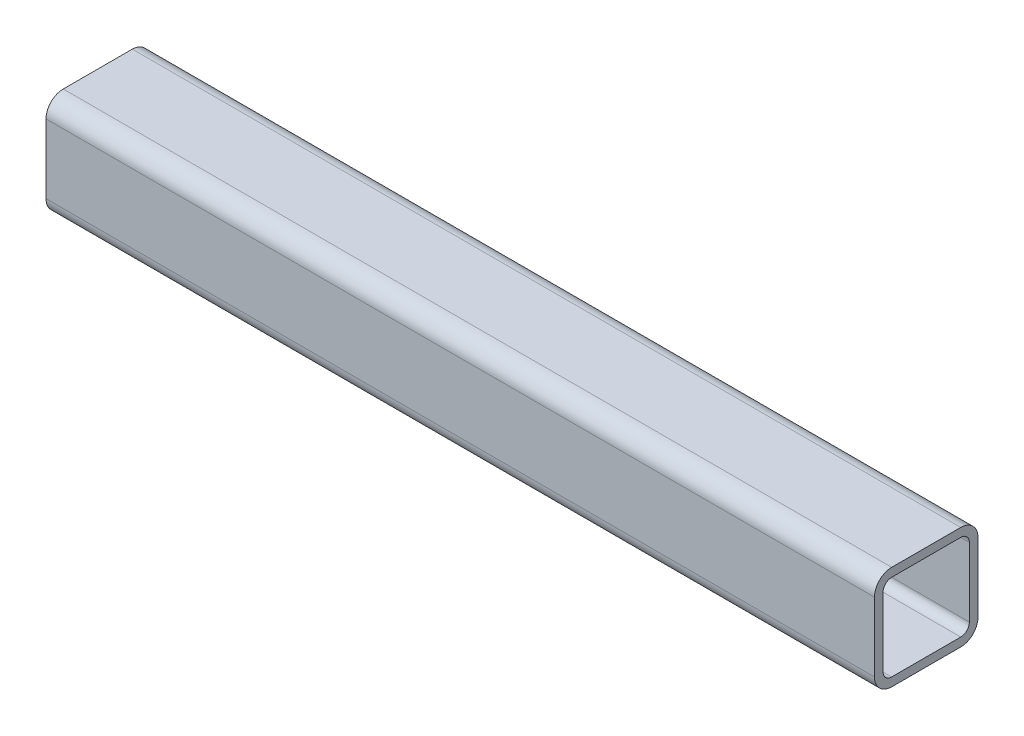
SolidWorks part; units mm, degrees
material "Plain Carbon Steel"
ref_plane "Front Plane" through (0, 0, 0) normal (0, 0, 1) x (1, 0, 0)
ref_plane "Top Plane" through (0, 0, 0) normal (0, 1, 0) x (1, 0, 0)
ref_plane "Right Plane" through (0, 0, 0) normal (1, 0, 0) x (0, 0, -1)
sketch3d "3DSketch1"
  line L0 (0, 0, 0) -> (-609.6, 0, 0)
  dimension "D1" = 609.6
other "Structural Member1"
ref_plane "Plane1" through (0, 0, 0) normal (-1, 0, 0) x (0, 0, 1)
sketch "Sketch1" plane through (0, 0, 0) normal (-1, 0, 0) x (0, 0, 1)
  line L0 (-25.4, -31.75) -> (25.4, -31.75)
  line L1 (-31.75, -25.4) -> (-31.75, 25.4)
  line L2 (25.4, 31.75) -> (-25.4, 31.75)
  line L3 (31.75, 25.4) -> (31.75, -25.4)
  line L4 (-25.4, -38.1) -> (25.4, -38.1)
  line L5 (-38.1, -25.4) -> (-38.1, 25.4)
  line L6 (25.4, 38.1) -> (-25.4, 38.1)
  line L7 (38.1, 25.4) -> (38.1, -25.4)
  line L8 (0, 0) -> (31.75, 0) construction
  line L9 (0, 0) -> (0, 31.75) construction
  arc A0 (38.1, 25.4) -> (25.4, 38.1) centre (25.4, 25.4) ccw
  arc A1 (25.4, -38.1) -> (38.1, -25.4) centre (25.4, -25.4) ccw
  arc A2 (-38.1, -25.4) -> (-25.4, -38.1) centre (-25.4, -25.4) ccw
  arc A3 (-25.4, 38.1) -> (-38.1, 25.4) centre (-25.4, 25.4) ccw
  arc A4 (-25.4, 31.75) -> (-31.75, 25.4) centre (-25.4, 25.4) ccw
  arc A5 (31.75, 25.4) -> (25.4, 31.75) centre (25.4, 25.4) ccw
  arc A6 (25.4, -31.75) -> (31.75, -25.4) centre (25.4, -25.4) ccw
  arc A7 (-31.75, -25.4) -> (-25.4, -31.75) centre (-25.4, -25.4) ccw
  point P3 (0, 38.1)
  point P4 (38.1, 0)
  point P5 (0, -38.1)
  point P6 (-38.1, 0)
  point P7 (-38.1, 38.1)
  point P8 (-38.1, -38.1)
  point P33 (0, 0)
  point P35 (38.1, -38.1)
  point P36 (38.1, 38.1)
  point P37 (0, 0)
  dimension "D1" = 12.7
  dimension "Thickness" = 6.35
  dimension "V_leg" = 76.2
